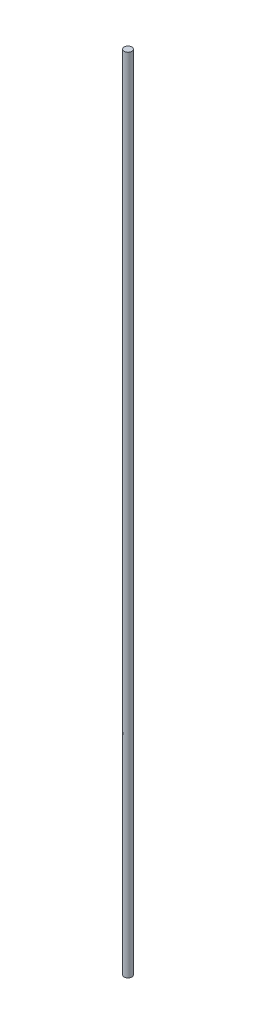
SolidWorks part; units mm, degrees
material "Nylon 101"
ref_plane "Front Plane" through (0, 0, 0) normal (0, 0, 1) x (1, 0, 0)
ref_plane "Top Plane" through (0, 0, 0) normal (0, 1, 0) x (1, 0, 0)
ref_plane "Right Plane" through (0, 0, 0) normal (1, 0, 0) x (0, 0, -1)
sketch "Sketch1" plane through (0, 0, 0) normal (0, 1, 0) x (1, 0, 0)
  circle A0 centre (0, 0) radius 1.65
  dimension "D1" = 3.3
extrude "Boss-Extrude1" add sketch "Sketch1" along normal blind 344
